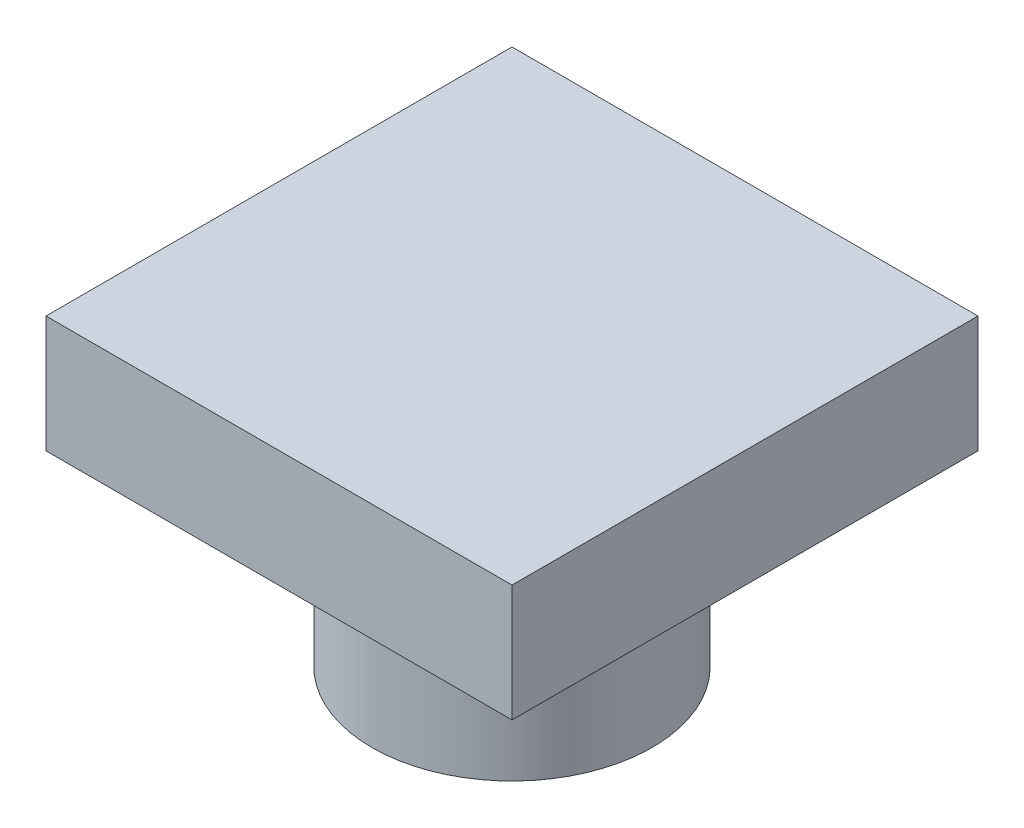
SolidWorks part; units mm, degrees
ref_plane "Alzado" through (0, 0, 0) normal (0, 0, 1) x (1, 0, 0)
ref_plane "Planta" through (0, 0, 0) normal (0, 1, 0) x (1, 0, 0)
ref_plane "Vista lateral" through (0, 0, 0) normal (1, 0, 0) x (0, 0, -1)
sketch "Croquis1" plane through (0, 0, 0) normal (1, 0, 0) x (0, 0, -1)
  line L0 (0, 0) -> (0, 19394.6636) construction
  line L3 (0, 0) -> (-6, 0)
  line L4 (-6, 0) -> (-6, 8)
  line L5 (-6, 8) -> (0, 8)
  line L6 (0, 8) -> (0, 0)
  dimension "D2" = 8
  dimension "D3" = 6
revolve "Revolución1" add sketch "Croquis1" angle 360 about L0
sketch "Croquis2" plane through (0, 8, 0) normal (0, 1, 0) x (1, 0, 0)
  line L5 (-9.975, -9.975) -> (9.975, -9.975)
  line L6 (-9.975, -9.975) -> (-9.975, 9.975)
  line L7 (-9.975, 9.975) -> (9.975, 9.975)
  line L8 (9.975, -9.975) -> (9.975, 9.975)
  line L9 (-9.975, -9.975) -> (9.975, 9.975) construction
  line L10 (-9.975, 9.975) -> (9.975, -9.975) construction
  point P0 (0, 0)
  dimension "D1" = 19.95
extrude "Saliente-Extruir1" add sketch "Croquis2" along normal blind 5 contours L5 L8 L7 L6
fillet "Redondeo4" [suppressed] radius 1.5
sketch "Sketch1" plane through (0, 0, 0) normal (1, 0, 0) x (0, 0, -1)
  line L0 (-6, 4) -> (0, 4) construction
  line L1 (-6, 8) -> (-6, 0) construction
  line L2 (0, 4) -> (0, 0) construction
  line L3 (-6, 0) -> (6, 0) construction
sketch "Sketch6" plane through (0, 0, 0) normal (0, -1, 0) x (1, 0, 0)
  circle A0 centre (0, 0) radius 4
  dimension "D1" = 8
extrude "Cut-Extrude1" cut sketch "Sketch6" against normal blind 10.5 contours A0
